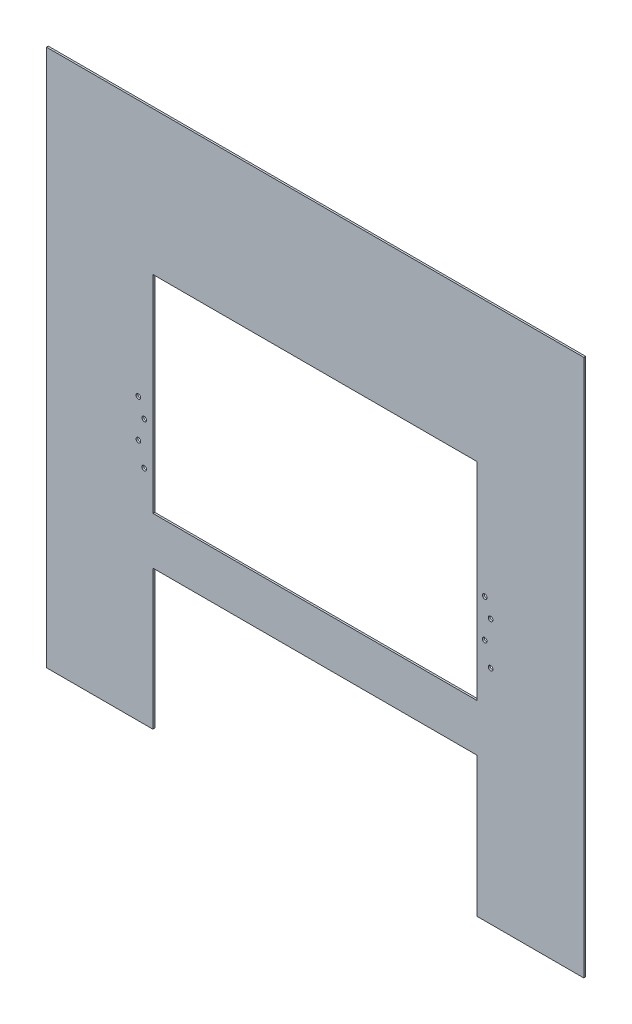
SolidWorks part; units mm, degrees
material "6061 合金"
ref_plane "前视基准面" through (0, 0, 0) normal (0, 0, 1) x (1, 0, 0)
ref_plane "上视基准面" through (0, 0, 0) normal (0, 1, 0) x (1, 0, 0)
ref_plane "右视基准面" through (0, 0, 0) normal (1, 0, 0) x (0, 0, -1)
sketch "草图1" plane through (0, 0, 0) normal (0, 0, 1) x (1, 0, 0)
  line L0 (70, 580) -> (650, 580)
  line L4 (185, 201.725) -> (535, 201.725)
  line L5 (185, 425) -> (185, 201.725)
  line L6 (535, 425) -> (535, 201.725)
  line L7 (535, 150.575) -> (535, 0)
  line L10 (185, 150.575) -> (185, 0)
  line L11 (185, 425) -> (535, 425)
  line L12 (70, 580) -> (70, 0)
  line L13 (70, 0) -> (185, 0)
  line L14 (185, 150.575) -> (535, 150.575)
  line L15 (650, 0) -> (535, 0)
  line L16 (650, 580) -> (650, 0)
  circle A4 centre (175.6203, 285.3) radius 2.5
  circle A5 centre (175.6203, 239.2797) radius 2.5
  circle A6 centre (169.3, 262.3) radius 2.5
  circle A7 centre (169.3, 303.1) radius 2.5
  circle A8 centre (549.4203, 285.3) radius 2.5
  circle A9 centre (549.4203, 239.2797) radius 2.5
  circle A10 centre (543.1, 262.3) radius 2.5
  circle A11 centre (543.1, 303.1) radius 2.5
extrude "凸台-拉伸1" add sketch "草图1" along normal blind 2
